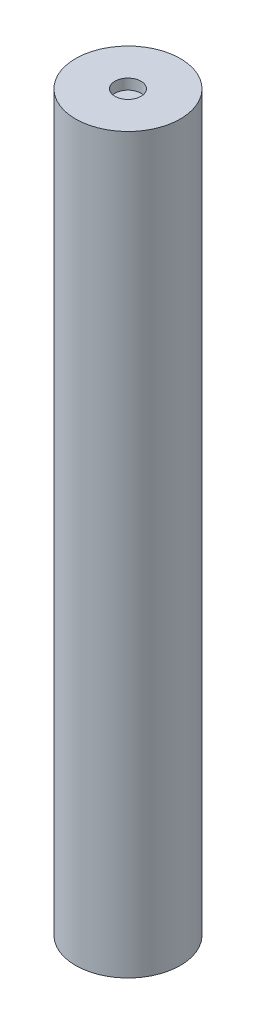
SolidWorks part; units mm, degrees
ref_plane "Front" through (0, 0, 0) normal (0, 0, 1) x (1, 0, 0)
ref_plane "Top" through (0, 0, 0) normal (0, 1, 0) x (1, 0, 0)
ref_plane "Right" through (0, 0, 0) normal (1, 0, 0) x (0, 0, -1)
sketch "Sketch1" plane through (0, 0, 0) normal (0, 1, 0) x (1, 0, 0)
  circle A0 centre (0, 0) radius 12.7
  dimension "D1" = 25.4
extrude "Boss-Extrude1" add sketch "Sketch1" along normal blind 177.8
sketch "Sketch2" plane through (0, 177.8, 0) normal (0, 1, 0) x (1, 0, 0)
  circle A0 centre (0, 0) radius 3.175
  dimension "D1" = 6.35
extrude "Cut-Extrude1" cut sketch "Sketch2" against normal blind 2.54
sketch "Sketch3" plane through (0, 0, 0) normal (0, -1, 0) x (1, 0, 0)
  circle A0 centre (0, 0) radius 3.175
  dimension "D1" = 6.35
extrude "Cut-Extrude2" cut sketch "Sketch3" against normal blind 2.54
